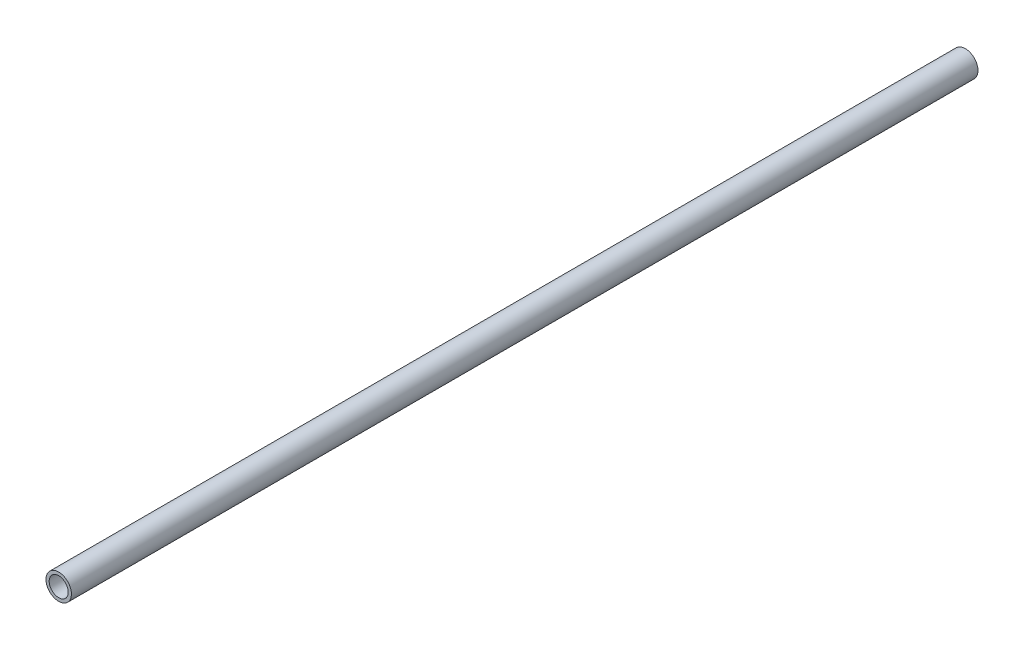
SolidWorks part; units mm, degrees
ref_plane "Plan de face" through (0, 0, 0) normal (0, 0, 1) x (1, 0, 0)
ref_plane "Plan de dessus" through (0, 0, 0) normal (0, 1, 0) x (1, 0, 0)
ref_plane "Plan de droite" through (0, 0, 0) normal (1, 0, 0) x (0, 0, -1)
sketch "Esquisse1" plane through (0, 0, 0) normal (0, 0, 1) x (1, 0, 0)
  circle A0 centre (0, 0) radius 4
  circle A1 centre (0, 0) radius 3
  dimension "D1" = 8
  dimension "D2" = 1
extrude "Boss.-Extru.1" add sketch "Esquisse1" along normal blind 285
